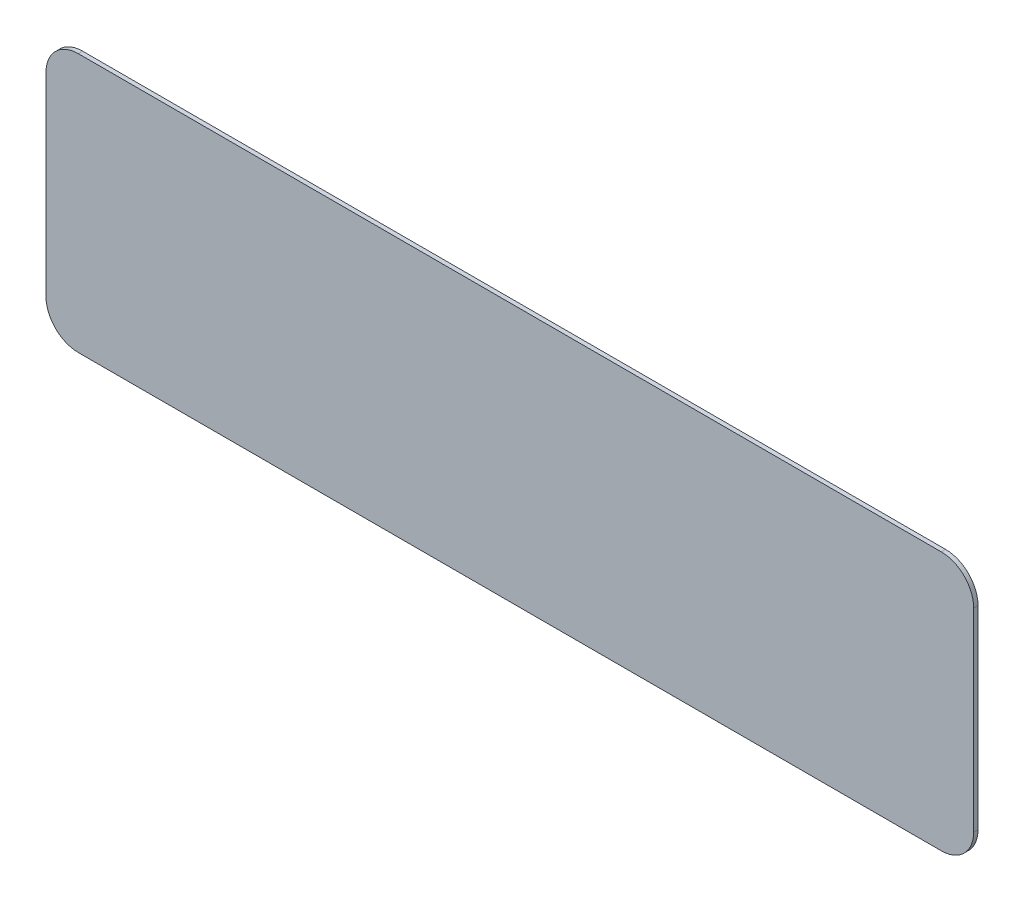
SolidWorks part; units mm, degrees
ref_plane "Front Plane" through (0, 0, 0) normal (0, 0, 1) x (1, 0, 0)
ref_plane "Top Plane" through (0, 0, 0) normal (0, 1, 0) x (1, 0, 0)
ref_plane "Right Plane" through (0, 0, 0) normal (1, 0, 0) x (0, 0, -1)
sketch "Sketch1" plane through (0, 0, 0) normal (0, 0, 1) x (1, 0, 0)
  line L0 (0, 0) -> (6.9721, 0) construction
  line L1 (-20, -6) -> (20, -6)
  line L2 (-21.5, -4.5) -> (-21.5, 4.5)
  line L3 (-20, 6) -> (20, 6)
  line L4 (21.5, -4.5) -> (21.5, 4.5)
  line L5 (0, 0) -> (0, 6) construction
  arc A0 (-20, -6) -> (-21.5, -4.5) centre (-20, -4.5) cw
  arc A1 (-21.5, 4.5) -> (-20, 6) centre (-20, 4.5) cw
  arc A2 (20, 6) -> (21.5, 4.5) centre (20, 4.5) cw
  arc A3 (20, -6) -> (21.5, -4.5) centre (20, -4.5) ccw
  dimension "D3" = 1.5
  dimension "D1" = 12
  dimension "D2" = 43
extrude "Boss-Extrude1" add sketch "Sketch1" along normal blind 0.2
